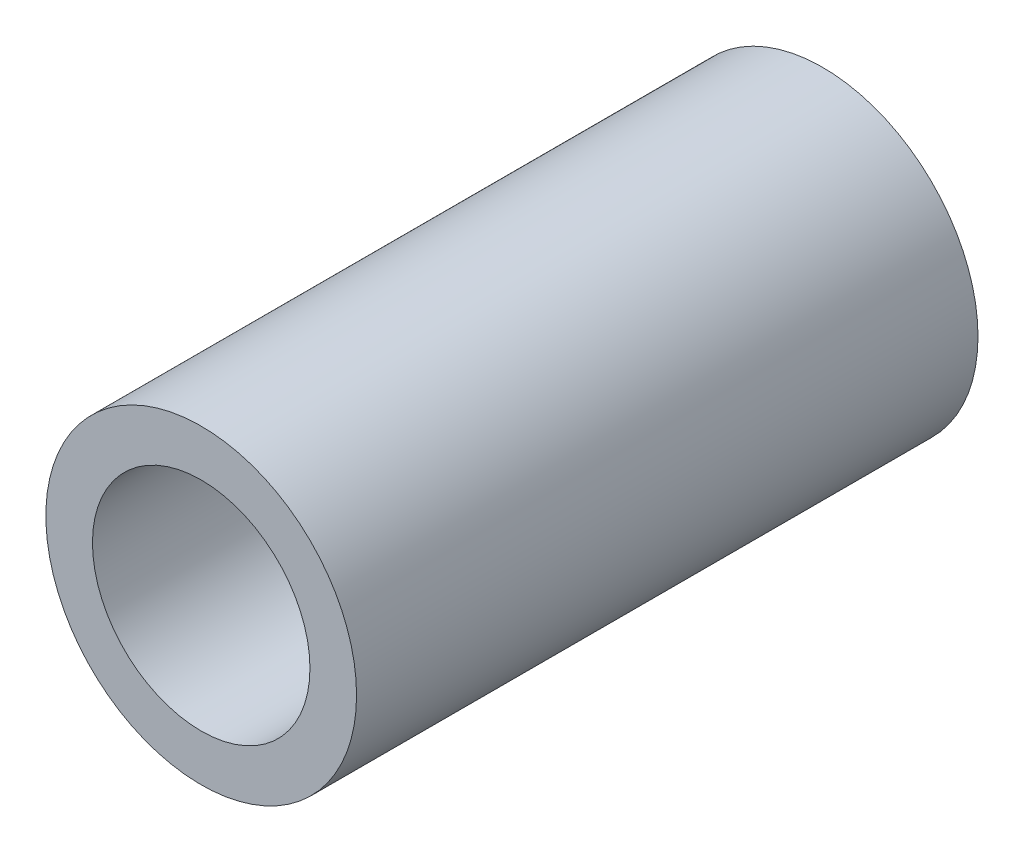
SolidWorks part; units mm, degrees
ref_plane "前视基准面" through (0, 0, 0) normal (0, 0, 1) x (1, 0, 0)
ref_plane "上视基准面" through (0, 0, 0) normal (0, 1, 0) x (1, 0, 0)
ref_plane "右视基准面" through (0, 0, 0) normal (1, 0, 0) x (0, 0, -1)
other "Configuration Table"
sketch "草图1" plane through (0, 0, 0) normal (0, 0, 1) x (1, 0, 0)
  circle A0 centre (0, 0) radius 2
  circle A1 centre (0, 0) radius 1.4
  dimension "D1" = 4
  dimension "D2" = 2.8
extrude "凸台-拉伸1" add sketch "草图1" along normal blind 8
